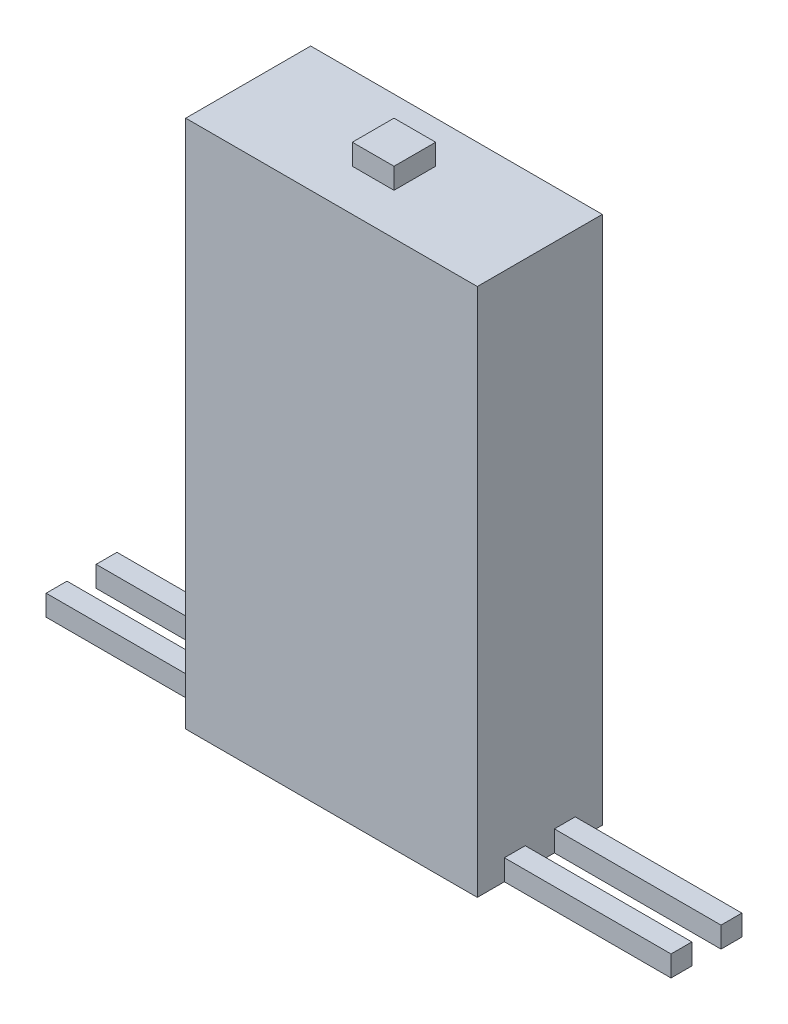
SolidWorks part; units mm, degrees
ref_plane "Front Plane" through (0, 0, 0) normal (0, 0, 1) x (1, 0, 0)
ref_plane "Top Plane" through (0, 0, 0) normal (0, 1, 0) x (1, 0, 0)
ref_plane "Right Plane" through (0, 0, 0) normal (1, 0, 0) x (0, 0, -1)
sketch "Sketch2" plane through (0, 0, 0) normal (0, 1, 0) x (1, 0, 0)
  line L1 (-35, -15) -> (35, -15)
  line L2 (-35, -15) -> (-35, 15)
  line L3 (-35, 15) -> (35, 15)
  line L4 (35, -15) -> (35, 15)
  line L5 (-35, -15) -> (35, 15) construction
  line L6 (-35, 15) -> (35, -15) construction
  point P0 (0, 0)
  dimension "D1" = 70
  dimension "D2" = 30
extrude "Boss-Extrude1" add sketch "Sketch2" along normal blind 127
sketch "Sketch3" plane through (35, 0, 0) normal (1, 0, 0) x (0, 0, -1)
  line L6 (-15, 0) -> (15, 0) construction
  line L21 (-3.5, 5) -> (-8.5, 5)
  line L22 (-3.5, 5) -> (-3.5, 0)
  line L23 (-3.5, 0) -> (-8.5, 0)
  line L24 (-8.5, 5) -> (-8.5, 0)
  line L26 (3.5, 5) -> (8.5, 5)
  line L27 (3.5, 5) -> (3.5, 0)
  line L28 (3.5, 0) -> (8.5, 0)
  line L29 (8.5, 5) -> (8.5, 0)
  point P2 (0, 2.5)
  point P3 (0, 2.5)
  dimension "D1" = 7
  dimension "D2" = 5
  dimension "D3" = 5
extrude "Boss-Extrude2" add sketch "Sketch3" along normal blind 40
sketch "Sketch4" plane through (-35, 0, 0) normal (-1, 0, 0) x (0, 0, 1)
  line L1 (-15, 0) -> (15, 0) construction
  line L8 (-3.5, 5) -> (-8.5, 5)
  line L9 (-3.5, 5) -> (-3.5, 0)
  line L10 (-3.5, 0) -> (-8.5, 0)
  line L11 (-8.5, 5) -> (-8.5, 0)
  line L13 (3.5, 5) -> (8.5, 5)
  line L14 (3.5, 5) -> (3.5, 0)
  line L15 (3.5, 0) -> (8.5, 0)
  line L16 (8.5, 5) -> (8.5, 0)
  point P3 (0, 2.5)
  dimension "D1" = 7
  dimension "D2" = 5
  dimension "D3" = 5
extrude "Boss-Extrude3" add sketch "Sketch4" along normal blind 40
sketch "Sketch5" plane through (0, 127, 0) normal (0, 1, 0) x (1, 0, 0)
  line L1 (-5, -5) -> (5, -5)
  line L2 (-5, -5) -> (-5, 5)
  line L3 (-5, 5) -> (5, 5)
  line L4 (5, -5) -> (5, 5)
  line L5 (-5, -5) -> (5, 5) construction
  line L6 (-5, 5) -> (5, -5) construction
  point P0 (0, 0)
  dimension "D1" = 10
  dimension "D2" = 10
extrude "Boss-Extrude4" add sketch "Sketch5" along normal blind 5
sketch "Sketch6" plane through (0, 0, 0) normal (0, -1, 0) x (-1, 0, 0)
  circle A0 centre (0, 0) radius 6
extrude "Cut-Extrude1" cut sketch "Sketch6" against normal blind 4
